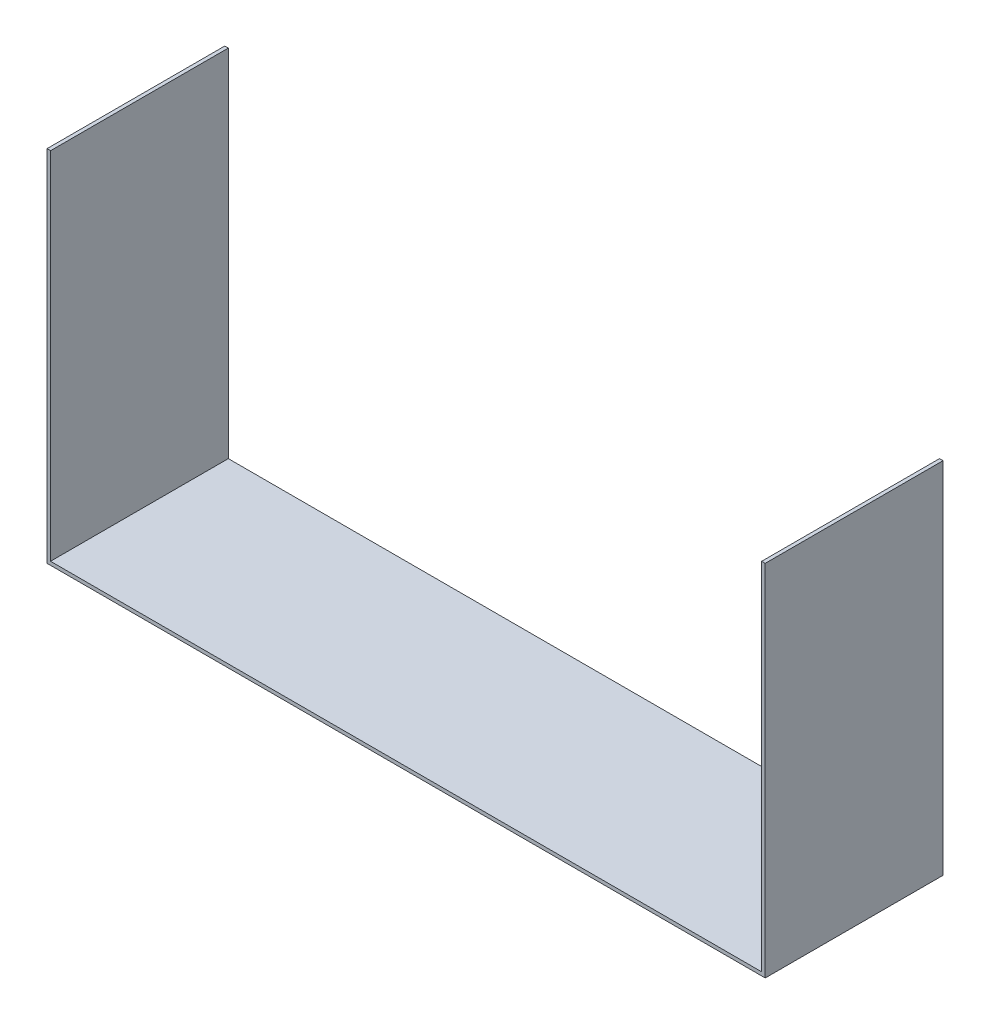
SolidWorks part; units mm, degrees
ref_plane "Front Plane" through (0, 0, 0) normal (0, 0, 1) x (1, 0, 0)
ref_plane "Top Plane" through (0, 0, 0) normal (0, 1, 0) x (1, 0, 0)
ref_plane "Right Plane" through (0, 0, 0) normal (1, 0, 0) x (0, 0, -1)
sketch "Sketch1" plane through (0, 0, 0) normal (0, 0, 1) x (1, 0, 0)
  line L0 (0, 0) -> (0, -20000)
  line L1 (0, -20000) -> (40000, -20000)
  line L2 (40000, -20000) -> (40000, 0)
  line L3 (-200, 0) -> (-200, -20200)
  line L4 (-200, -20200) -> (40200, -20200)
  line L5 (40200, -20200) -> (40200, 0)
  line L6 (-200, 0) -> (0, 0)
  line L7 (40000, 0) -> (40200, 0)
extrude "Boss-Extrude1" add sketch "Sketch1" along normal blind 10000
